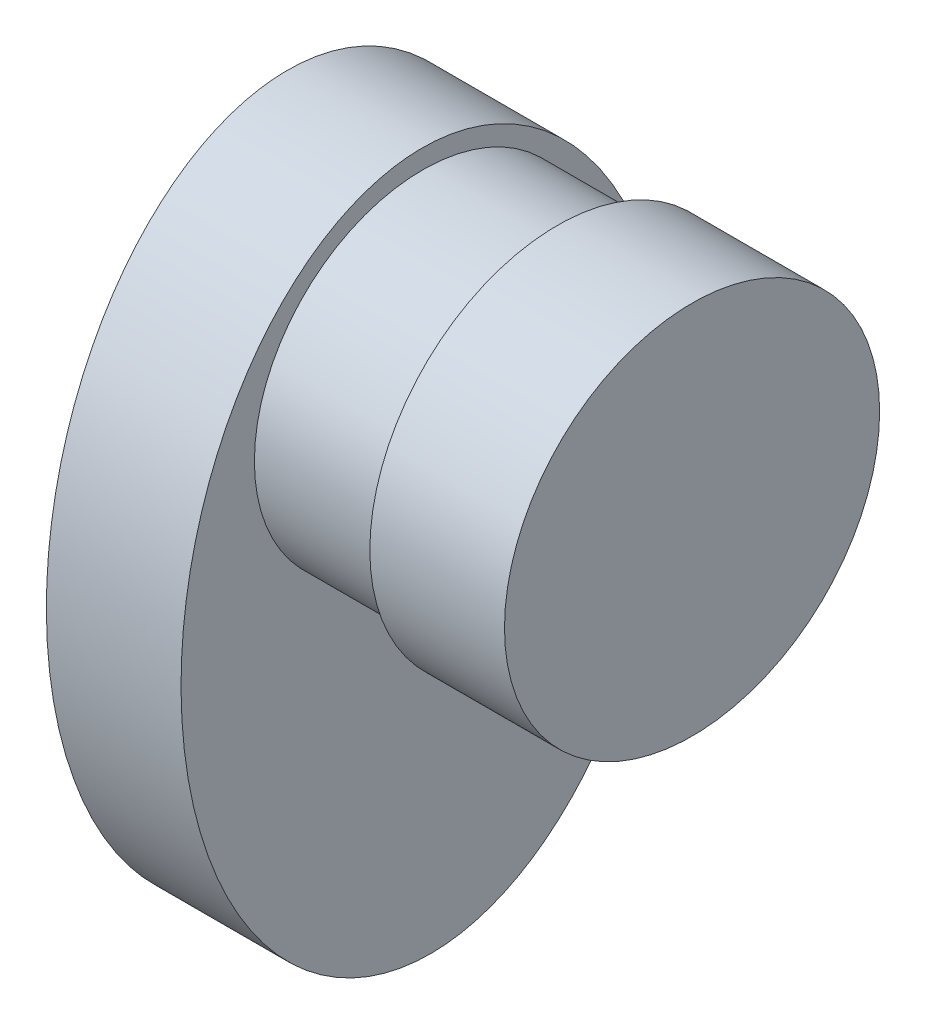
SolidWorks part; units mm, degrees
ref_plane "Front Plane" through (0, 0, 0) normal (0, 0, 1) x (1, 0, 0)
ref_plane "Top Plane" through (0, 0, 0) normal (0, 1, 0) x (1, 0, 0)
ref_plane "Right Plane" through (0, 0, 0) normal (1, 0, 0) x (0, 0, -1)
sketch "Sketch1" plane through (0, 0, 0) normal (1, 0, 0) x (0, 0, -1)
  circle A0 centre (0, 0) radius 495.3
  dimension "D1" = 990.6
extrude "Boss-Extrude1" add sketch "Sketch1" against normal blind 355.6
sketch "Sketch2" plane through (-355.6, 0, 0) normal (-1, 0, 0) x (0, 0, 1)
  circle A0 centre (0, 0) radius 444.5
  dimension "D1" = 889
extrude "Boss-Extrude2" add sketch "Sketch2" along normal blind 355.6
sketch "Sketch3" plane through (-711.2, 0, 0) normal (-1, 0, 0) x (0, 0, 1)
  line L0 (0, 0) -> (325.0311, 0) construction
  line L1 (0, -431.8) -> (236.8871, -431.8) construction
  circle A0 centre (0, 0) radius 495.3 construction
  ellipse E0 centre (-9.6384, -431.6924) end of major axis (-30.3325, -1358.5614) minor radius 647.7
  dimension "D1" = 431.8
extrude "Boss-Extrude3" add sketch "Sketch3" along normal blind 355.6
